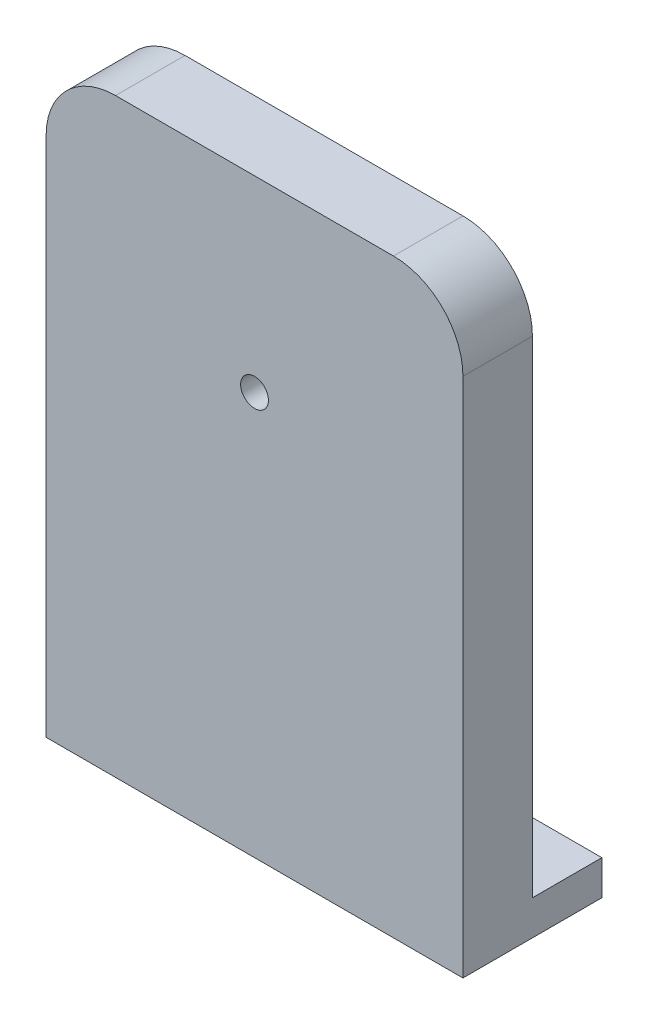
SolidWorks part; units mm, degrees
ref_plane "Front Plane" through (0, 0, 0) normal (0, 0, 1) x (1, 0, 0)
ref_plane "Top Plane" through (0, 0, 0) normal (0, 1, 0) x (1, 0, 0)
ref_plane "Right Plane" through (0, 0, 0) normal (1, 0, 0) x (0, 0, -1)
sketch "Sketch1" plane through (0, 0, 0) normal (0, 1, 0) x (1, 0, 0)
  line L0 (-16.8, 5) -> (-5, 5) construction
  line L1 (-30, 10) -> (30, 10)
  line L2 (-30, 10) -> (-30, -10)
  line L3 (-30, -10) -> (30, -10)
  line L4 (30, 10) -> (30, -10)
  line L5 (-30, 10) -> (30, -10) construction
  line L6 (-30, -10) -> (30, 10) construction
  line L7 (-16.8, 8.4) -> (-5, 8.4)
  line L8 (-16.8, 1.6) -> (-5, 1.6)
  line L9 (3.2, 5) -> (15, 5) construction
  line L10 (3.2, 8.4) -> (15, 8.4)
  line L11 (3.2, 1.6) -> (15, 1.6)
  arc A0 (-16.8, 8.4) -> (-16.8, 1.6) centre (-16.8, 5) ccw
  arc A1 (-5, 1.6) -> (-5, 8.4) centre (-5, 5) ccw
  arc A2 (3.2, 8.4) -> (3.2, 1.6) centre (3.2, 5) ccw
  arc A3 (15, 1.6) -> (15, 8.4) centre (15, 5) ccw
  point P0 (0, 0)
  point P8 (-10.9, 5)
  point P16 (9.1, 5)
  dimension "D3" = 3.4
  dimension "D1" = 60
  dimension "D2" = 20
  dimension "D4" = 35
  dimension "D5" = 15
  dimension "D6" = 2
extrude "Boss-Extrude1" add sketch "Sketch1" along normal blind 5
sketch "Sketch2" plane through (0, 5, 0) normal (0, 1, 0) x (1, 0, 0)
  line L0 (-30, 0) -> (30, 0)
  line L1 (-30, 10) -> (-30, -10) construction
  line L2 (30, -10) -> (30, 10) construction
  line L3 (30, 0) -> (30, -10)
  line L4 (30, -10) -> (-30, -10)
  line L5 (-30, -10) -> (-30, 0)
  dimension "D1" = 10
extrude "Boss-Extrude2" add sketch "Sketch2" along normal blind 80
sketch "Sketch3" plane through (0, 0, 0) normal (0, 0, -1) x (-1, 0, 0)
  line L0 (-30, 0) -> (30, 0) construction
  circle A0 centre (0, 58) radius 7.5
  dimension "D1" = 15
  dimension "D2" = 58
extrude "Cut-Extrude1" cut sketch "Sketch3" against normal blind 5
fillet "Fillet1" radius 10 2 edges at (30, 85, 5) (-30, 85, 5)
sketch "Sketch4" plane through (0, 0, 5) normal (0, 0, -1) x (-1, 0, 0)
  circle A0 centre (0, 58) radius 2
  circle A2 centre (0, 58) radius 7.5 construction
  dimension "D1" = 4
extrude "Cut-Extrude2" cut sketch "Sketch4" against normal through all
